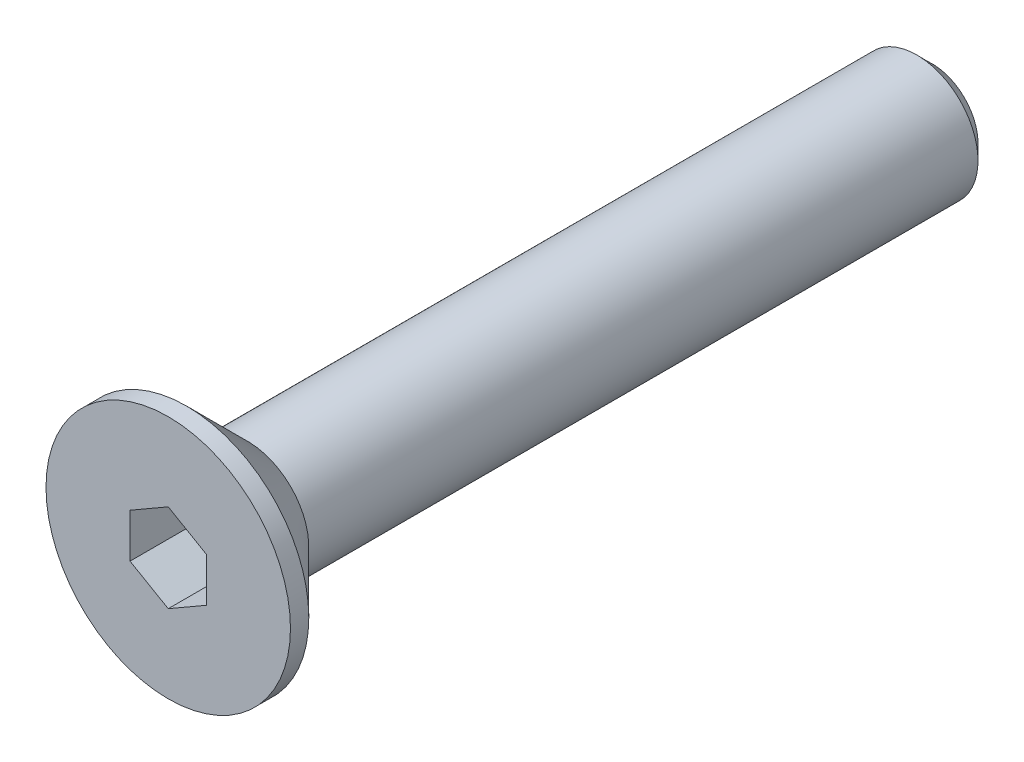
SolidWorks part; units mm, degrees
ref_plane "前视基准面" through (0, 0, 0) normal (0, 0, 1) x (1, 0, 0)
ref_plane "上视基准面" through (0, 0, 0) normal (0, 1, 0) x (1, 0, 0)
ref_plane "右视基准面" through (0, 0, 0) normal (1, 0, 0) x (0, 0, -1)
sketch "草图1" plane through (0, 0, 0) normal (1, 0, 0) x (0, 0, -1)
  line L0 (-12.5, 0) -> (-12.5, 4)
  line L1 (-12.5, 4) -> (-11.9, 4)
  line L2 (-11.9, 4) -> (-9.9, 2)
  line L3 (-9.9, 2) -> (12.5, 2)
  line L5 (12.5, 2) -> (12.5, 0)
  line L6 (12.5, 0) -> (-12.5, 0)
  dimension "D1" = 45
  dimension "D2" = 2
  dimension "D3" = 25
  dimension "D4" = 4
  dimension "D5" = 2.6
revolve "旋转1" add sketch "草图1" angle 360 about L6
chamfer "倒角1" distance 0.5 angle 45 1 edges at (-2, 0, -12.5)
sketch "草图2" plane through (0, 0, 12.5) normal (0, 0, 1) x (1, 0, 0)
  line L1 (0, 1.4434) -> (-1.25, 0.7217)
  line L2 (-1.25, 0.7217) -> (-1.25, -0.7217)
  line L3 (-1.25, -0.7217) -> (0, -1.4434)
  line L4 (0, -1.4434) -> (1.25, -0.7217)
  line L5 (1.25, -0.7217) -> (1.25, 0.7217)
  line L6 (1.25, 0.7217) -> (0, 1.4434)
  circle A0 centre (0, 0) radius 1.25 construction
  dimension "D1" = 2.5
extrude "切除-拉伸1" cut sketch "草图2" against normal blind 2.5
